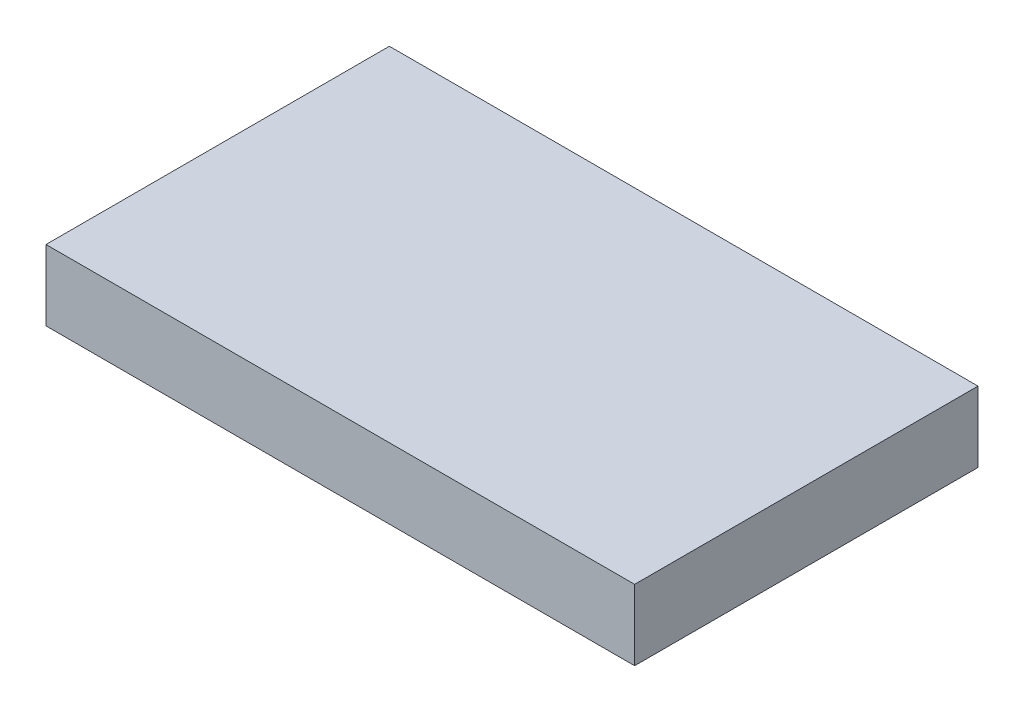
SolidWorks part; units mm, degrees
material "Pine"
ref_plane "Front Plane" through (0, 0, 0) normal (0, 0, 1) x (1, 0, 0)
ref_plane "Top Plane" through (0, 0, 0) normal (0, 1, 0) x (1, 0, 0)
ref_plane "Right Plane" through (0, 0, 0) normal (1, 0, 0) x (0, 0, -1)
sketch "Sketch1" plane through (0, 0, 0) normal (0, 1, 0) x (1, 0, 0)
  line L1 (76.2, 44.45) -> (-76.2, 44.45)
  line L2 (76.2, 44.45) -> (76.2, -44.45)
  line L3 (76.2, -44.45) -> (-76.2, -44.45)
  line L4 (-76.2, 44.45) -> (-76.2, -44.45)
  line L5 (0, -44.45) -> (0, 44.45) construction
  line L6 (76.2, 0) -> (-76.2, 0) construction
  point P0 (0, 0)
  dimension "D1" = 88.9
  dimension "D2" = 152.4
extrude "Boss-Extrude1" add sketch "Sketch1" along normal blind 18.2562
